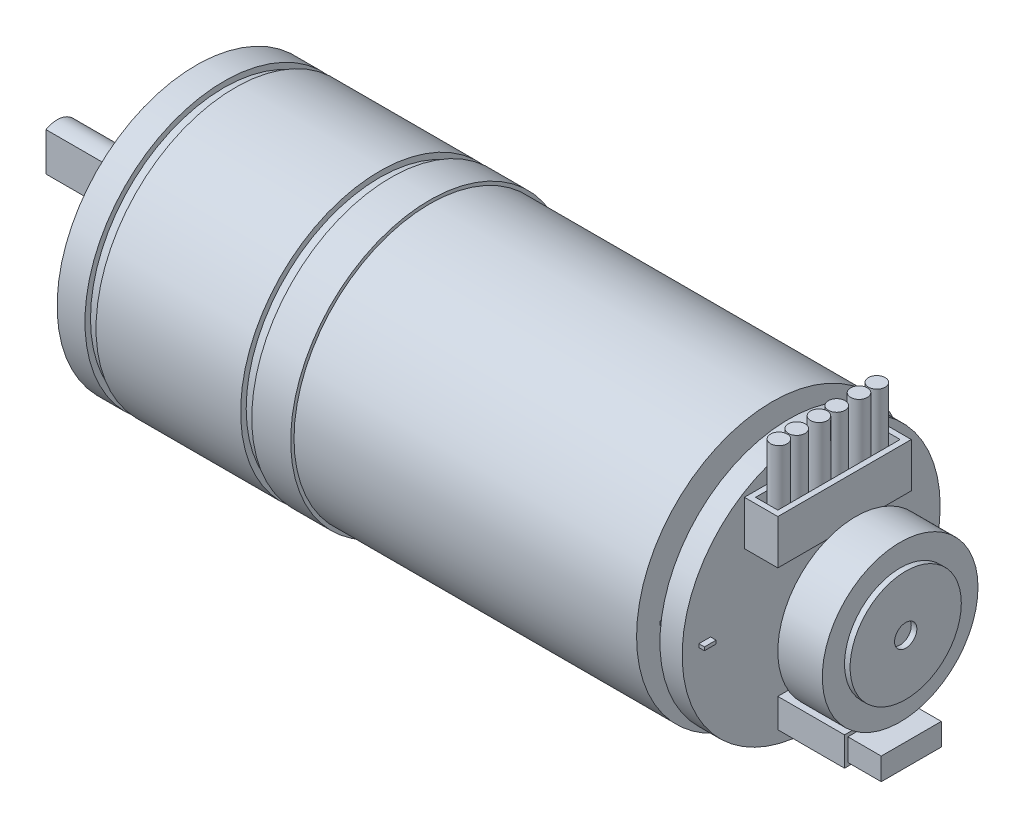
SolidWorks part; units mm, degrees
ref_plane "Alzado" through (0, 0, 0) normal (0, 0, 1) x (1, 0, 0)
ref_plane "Planta" through (0, 0, 0) normal (0, 1, 0) x (1, 0, 0)
ref_plane "Vista lateral" through (0, 0, 0) normal (1, 0, 0) x (0, 0, -1)
sketch "Croquis1" plane through (0, 0, 0) normal (0, 0, 1) x (1, 0, 0)
  line L0 (0, 0) -> (30.8, 0) construction
  line L1 (0, 0) -> (0, 12.2)
  line L2 (0, 12.2) -> (30.8, 12.2)
  line L3 (30.8, 12.2) -> (30.8, 0)
  dimension "D1" = 30.8
  dimension "D2" = 12.2
revolve "Revolución-Lámina1" add sketch "Croquis1" angle 360 about L0
sketch "Croquis3" plane through (0, 0, 0) normal (-1, 0, 0) x (0, 0, 1)
  circle A0 centre (0, 0) radius 12.5
  dimension "D1" = 25
extrude "Saliente-Extruir1" add sketch "Croquis3" along normal blind 21
ref_plane "Plano1" through (30.8, 0, 0) normal (1, 0, 0) x (0, 0, -1)
ref_plane "Plano3" through (-21, 0, 0) normal (1, 0, 0) x (0, 0, -1)
ref_plane "Plano4" through (-17.5, 0, 0) normal (1, 0, 0) x (0, 0, -1)
sketch "Croquis6" plane through (-17.5, 0, 0) normal (1, 0, 0) x (0, 0, -1)
  circle A0 centre (0, 0) radius 12
  circle A1 centre (0, 0) radius 12.5
  dimension "D1" = 24
  dimension "D2" = 25
extrude "Cortar-Extruir3" cut sketch "Croquis6" against normal blind 1
ref_plane "Plano5" through (-3.5, 0, 0) normal (1, 0, 0) x (0, 0, -1)
sketch "Croquis7" plane through (-3.5, 0, 0) normal (1, 0, 0) x (0, 0, -1)
  circle A0 centre (0, 0) radius 12.5
  circle A1 centre (0, 0) radius 12
  dimension "D1" = 24
  dimension "D2" = 25
extrude "Cortar-Extruir4" cut sketch "Croquis7" against normal blind 1
sketch "Croquis8" plane through (-21, 0, 0) normal (-1, 0, 0) x (0, 0, 1)
  circle A0 centre (0, 0) radius 3.5
  dimension "D1" = 7
extrude "Saliente-Extruir3" add sketch "Croquis8" along normal blind 2.5
sketch "Croquis9" plane through (-21, 0, 0) normal (-1, 0, 0) x (0, 0, 1)
  circle A0 centre (0, 0) radius 2
  dimension "D1" = 4
extrude "Saliente-Extruir4" add sketch "Croquis9" along normal blind 12.5
ref_plane "Plano6" through (0, 0, 1) normal (0, 0, 1) x (1, 0, 0)
sketch "Croquis10" plane through (0, 0, 1) normal (0, 0, 1) x (1, 0, 0)
  line L0 (-33.5, -2) -> (-23.5, -2) construction
  line L1 (-33.5, 2) -> (-25.5, 2)
  line L2 (-33.5, 2) -> (-33.5, -2)
  line L3 (-33.5, -2) -> (-25.5, -2)
  line L4 (-25.5, 2) -> (-25.5, -2)
  dimension "D1" = 8
extrude "Cortar-Extruir5" cut sketch "Croquis10" along normal blind 5
sketch "Croquis11" plane through (-21, 0, 0) normal (-1, 0, 0) x (0, 0, 1)
  line L0 (0, 0) -> (-8, 0) construction
  line L1 (0, 0) -> (8, 0) construction
  circle A0 centre (-8, 0) radius 1.5
  circle A1 centre (8, 0) radius 1.5
  dimension "D3" = 3
  dimension "D4" = 3
  dimension "D1" = 8
  dimension "D2" = 8
extrude "Cortar-Extruir6" cut sketch "Croquis11" against normal blind 3
sketch "Croquis12" plane through (-21, 0, 0) normal (-1, 0, 0) x (0, 0, 1)
  line L0 (0, 0) -> (0, -8.5) construction
  line L1 (0, 0) -> (0, 8.5) construction
  circle A0 centre (0, -8.5) radius 2
  circle A1 centre (0, 8.5) radius 2
  dimension "D3" = 4
  dimension "D4" = 4
  dimension "D1" = 8.5
  dimension "D2" = 8.5
extrude "Cortar-Extruir7" cut sketch "Croquis12" against normal blind 3
sketch "Croquis14" plane through (-18, 0, 0) normal (-1, 0, 0) x (0, 0, 1)
  line L0 (0, 8.5) -> (-0.25, 8.5) construction
  line L1 (0, 8.5) -> (0.25, 8.5) construction
  line L2 (0, 8.5) -> (0, 8.75) construction
  line L3 (0, 8.5) -> (0, 8.25) construction
  line L9 (-0.25, 8.25) -> (-0.25, 7.2)
  line L10 (-0.25, 7.2) -> (0.25, 7.2)
  line L11 (0.25, 7.2) -> (0.25, 8.25)
  line L12 (0.25, 8.25) -> (1.3, 8.25)
  line L13 (1.3, 8.25) -> (1.3, 8.75)
  line L14 (1.3, 8.75) -> (0.25, 8.75)
  line L15 (0.25, 8.75) -> (0.25, 9.8)
  line L16 (0.25, 9.8) -> (-0.25, 9.8)
  line L17 (-0.25, 9.8) -> (-0.25, 8.75)
  line L18 (-0.25, 8.75) -> (-1.3, 8.75)
  line L19 (-1.3, 8.75) -> (-1.3, 8.25)
  line L20 (-1.3, 8.25) -> (-0.25, 8.25)
extrude "Cortar-Extruir8" cut sketch "Croquis14" against normal blind 1.5
sketch "Croquis15" plane through (-18, 0, 0) normal (-1, 0, 0) x (0, 0, 1)
  line L0 (0, -8.5) -> (-0.25, -8.5) construction
  line L1 (0, -8.5) -> (0.25, -8.5) construction
  line L2 (0, -8.5) -> (0, -8.25) construction
  line L3 (0, -8.5) -> (0, -8.75) construction
  line L9 (-0.25, -8.75) -> (-0.25, -9.8)
  line L10 (-0.25, -9.8) -> (0.25, -9.8)
  line L11 (0.25, -9.8) -> (0.25, -8.75)
  line L12 (0.25, -8.75) -> (1.3, -8.75)
  line L13 (1.3, -8.75) -> (1.3, -8.25)
  line L14 (1.3, -8.25) -> (0.25, -8.25)
  line L15 (0.25, -8.25) -> (0.25, -7.2)
  line L16 (0.25, -7.2) -> (-0.25, -7.2)
  line L17 (-0.25, -7.2) -> (-0.25, -8.25)
  line L18 (-0.25, -8.25) -> (-1.3, -8.25)
  line L19 (-0.25, -8.75) -> (-1.3, -8.75)
  line L20 (-1.3, -8.75) -> (-1.3, -8.25)
  dimension "D1" = 1.05
  dimension "D2" = 0.25
  dimension "D3" = 1.05
  dimension "D4" = 1.05
  dimension "D5" = 1.05
extrude "Cortar-Extruir9" cut sketch "Croquis15" against normal blind 1.5
fillet "Redondeo1" radius 0.25 2 edges at (-18, 8.5, 2) (-18, -8.5, 2)
sketch "Croquis16" plane through (30.8, 0, 0) normal (1, 0, 0) x (0, 0, -1)
  line L0 (0, 0) -> (-9.05, 0) construction
  line L1 (0, 0) -> (9.05, 0) construction
  line L2 (8, -0.15) -> (8, 0.15)
  line L3 (-9.05, 0) -> (-8, 0)
  line L5 (9.05, 0) -> (10.1, 0)
  line L6 (-10.1, -0.15) -> (-10.1, 0.15)
  line L7 (-10.1, 0.15) -> (-9.05, 0.15)
  line L8 (-9.05, 0.15) -> (-9.05, -0.15)
  line L9 (-9.05, -0.15) -> (-10.1, -0.15)
  line L10 (8, 0.15) -> (9.05, 0.15)
  line L11 (9.05, 0.15) -> (9.05, -0.15)
  line L12 (9.05, -0.15) -> (8, -0.15)
  dimension "D1" = 9.05
  dimension "D2" = 9.05
extrude "Saliente-Extruir5" add sketch "Croquis16" along normal blind 4 contours L9 L8 L7 L6 | L12 L11 L10 L2
sketch "Croquis17" plane through (30.8, 0, 0) normal (1, 0, 0) x (0, 0, -1)
  circle A0 centre (0, 0) radius 4
  dimension "D1" = 8
extrude "Saliente-Extruir6" add sketch "Croquis17" along normal blind 0.75
sketch "Croquis18" plane through (31.55, 0, 0) normal (1, 0, 0) x (0, 0, -1)
  circle A0 centre (0, 0) radius 3.5
  dimension "D1" = 7
extrude "Saliente-Extruir7" add sketch "Croquis18" along normal blind 0.75
sketch "Croquis19" plane through (32.3, 0, 0) normal (1, 0, 0) x (0, 0, -1)
  circle A0 centre (0, 0) radius 11.6
  dimension "D1" = 23.2
extrude "Saliente-Extruir8" add sketch "Croquis19" along normal blind 2
sketch "Croquis20" plane through (34.3, 0, 0) normal (1, 0, 0) x (0, 0, -1)
  circle A0 centre (0, 0) radius 1
  dimension "D1" = 2
extrude "Saliente-Extruir9" add sketch "Croquis20" along normal blind 4
sketch "Croquis21" plane through (38.3, 0, 0) normal (1, 0, 0) x (0, 0, -1)
  circle A0 centre (0, 0) radius 7
  dimension "D1" = 14
extrude "Saliente-Extruir10" add sketch "Croquis21" along normal blind 4
sketch "Croquis22" plane through (42.3, 0, 0) normal (1, 0, 0) x (0, 0, -1)
  circle A0 centre (0, 0) radius 5
  dimension "D1" = 10
extrude "Saliente-Extruir11" add sketch "Croquis22" along normal blind 0.5
sketch "Croquis23" plane through (42.8, 0, 0) normal (1, 0, 0) x (0, 0, -1)
  circle A0 centre (0, 0) radius 1
  dimension "D1" = 2
extrude "Cortar-Extruir10" cut sketch "Croquis23" against normal blind 0.5
sketch "Croquis24" plane through (34.3, 0, 0) normal (1, 0, 0) x (0, 0, -1)
  line L0 (0, 11.6) -> (0, 9.5) construction
  line L1 (0, 9.5) -> (6, 9.5)
  line L2 (0, 9.5) -> (-6, 9.5)
  line L3 (-6, 9.5) -> (-6, 5.5)
  line L4 (-6, 5.5) -> (6, 5.5)
  line L5 (6, 5.5) -> (6, 9.5)
  circle A0 centre (0, 0) radius 11.6 construction
  dimension "D1" = 2.1
  dimension "D2" = 6
  dimension "D3" = 6
  dimension "D4" = 4
extrude "Saliente-Extruir12" add sketch "Croquis24" along normal blind 3
sketch "Croquis25" plane through (0, 9.5, 0) normal (0, 1, 0) x (1, 0, 0)
  line L0 (35.8, -6) -> (35.8, -5.5) construction
  line L1 (37.3, -6) -> (34.3, -6) construction
  line L2 (37.3, 0) -> (36.8, 0) construction
  line L3 (37.3, 6) -> (37.3, -6) construction
  line L4 (36.8, -5.5) -> (36.8, 5.5)
  line L5 (35.8, -5.5) -> (36.8, -5.5)
  line L6 (36.8, 5.5) -> (34.8, 5.5)
  line L7 (35.8, 6) -> (35.8, 5.5) construction
  line L8 (37.3, 6) -> (34.3, 6) construction
  line L9 (34.8, 5.5) -> (34.8, -5.5)
  line L10 (34.8, -5.5) -> (35.8, -5.5)
  dimension "D1" = 0.5
  dimension "D2" = 0.5
  dimension "D3" = 0.5
  dimension "D4" = 2
extrude "Cortar-Extruir11" cut sketch "Croquis25" against normal blind 3.5
sketch "Croquis26" plane through (0, 6, 0) normal (0, 1, 0) x (1, 0, 0)
  line L0 (35.8, -5.5) -> (35.8, -4.4) construction
  line L1 (34.8, -5.5) -> (36.8, -5.5) construction
  line L2 (35.8, -4.4) -> (35.8, -2.8) construction
  line L3 (35.8, -2.8) -> (35.8, -0.8) construction
  line L4 (35.8, -0.8) -> (35.8, 0.8) construction
  line L5 (35.8, 0.8) -> (35.8, 2.8) construction
  line L6 (35.8, 2.8) -> (35.8, 4.4) construction
  circle A0 centre (35.8, -4.4) radius 0.75
  circle A1 centre (35.8, -2.8) radius 0.75
  circle A2 centre (35.8, -0.8) radius 0.75
  circle A3 centre (35.8, 0.8) radius 0.75
  circle A4 centre (35.8, 2.8) radius 0.75
  circle A5 centre (35.8, 4.4) radius 0.75
  dimension "D2" = 1.5
  dimension "D4" = 1.5
  dimension "D6" = 1.5
  dimension "D8" = 1.5
  dimension "D10" = 1.5
  dimension "D12" = 1.5
  dimension "D1" = 1.1
  dimension "D3" = 1.6
  dimension "D5" = 2
  dimension "D7" = 1.6
  dimension "D9" = 2
  dimension "D11" = 1.6
extrude "Saliente-Extruir13" add sketch "Croquis26" along normal blind 8
sketch "Croquis27" plane through (34.3, 0, 0) normal (1, 0, 0) x (0, 0, -1)
  line L0 (0, -11.6) -> (0, -10.1) construction
  line L1 (0, -10.1) -> (3, -10.1)
  line L2 (0, -10.1) -> (-3, -10.1)
  line L3 (-3, -10.1) -> (-3, -7.5)
  line L4 (-3, -7.5) -> (3, -7.5)
  line L5 (3, -7.5) -> (3, -10.1)
  circle A0 centre (0, 0) radius 11.6 construction
  dimension "D1" = 1.5
  dimension "D2" = 3
  dimension "D3" = 3
  dimension "D4" = 2.6
extrude "Saliente-Extruir14" add sketch "Croquis27" along normal blind 6
sketch "Croquis28" plane through (40.3, 0, 0) normal (1, 0, 0) x (0, 0, -1)
  line L0 (3, -7.5) -> (-3, -7.5) construction
  line L1 (-2.7, -7.8) -> (2.7, -7.8)
  line L2 (-2.7, -7.8) -> (-2.7, -9.8)
  line L3 (-2.7, -9.8) -> (2.7, -9.8)
  line L4 (2.7, -7.8) -> (2.7, -9.8)
  line L5 (-3, -7.5) -> (-3, -10.1) construction
  line L6 (-3, -10.1) -> (3, -10.1) construction
  line L7 (3, -10.1) -> (3, -7.5) construction
  dimension "D1" = 0.3
  dimension "D2" = 0.3
  dimension "D3" = 0.3
  dimension "D4" = 0.3
extrude "Saliente-Extruir15" add sketch "Croquis28" along normal blind 3
